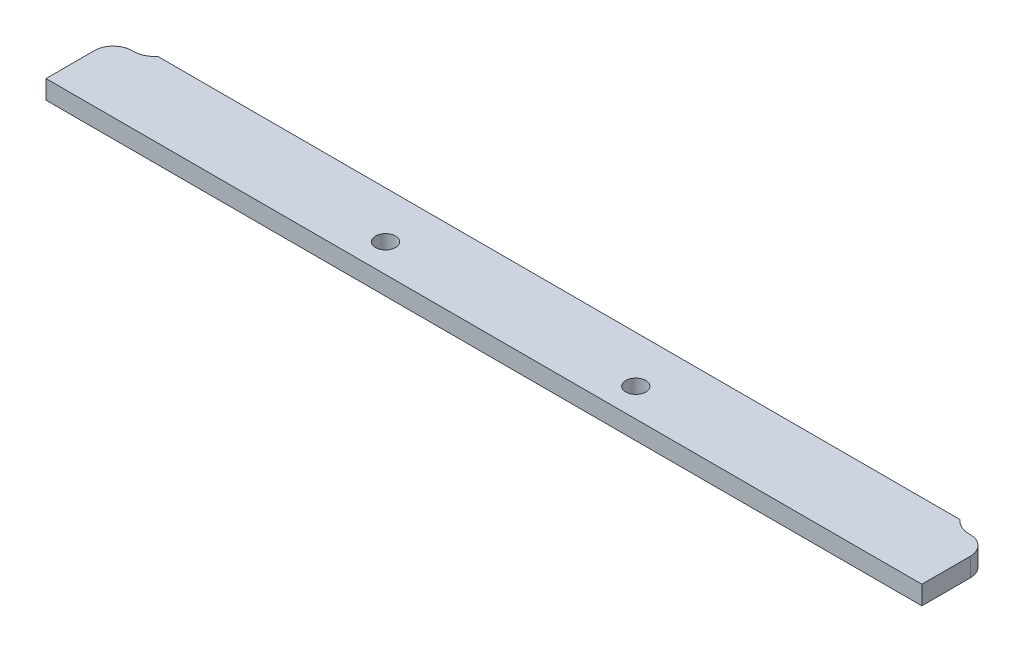
SolidWorks part; units mm, degrees
ref_plane "Front Plane" through (0, 0, 0) normal (0, 0, 1) x (1, 0, 0)
ref_plane "Top Plane" through (0, 0, 0) normal (0, 1, 0) x (1, 0, 0)
ref_plane "Right Plane" through (0, 0, 0) normal (1, 0, 0) x (0, 0, -1)
sketch "Sketch1" plane through (0, 0, 0) normal (0, 1, 0) x (1, 0, 0)
  line L0 (-5.431, 25.0999) -> (-5.6253, 25.0999) construction
  line L1 (128.3747, 25.0999) -> (128.1804, 25.0999) construction
  line L2 (131.3747, 22.0999) -> (131.3747, -33.8347) construction
  line L3 (131.3747, 14.3589) -> (-8.6253, 14.3589) construction
  line L4 (-8.6253, -33.8347) -> (-8.6253, 22.0999) construction
  line L5 (-2.7409, 26.3608) -> (125.4903, 26.3608) construction
  line L6 (-5.431, 25.0999) -> (-5.6253, 25.0999)
  line L7 (128.3747, 25.0999) -> (128.1804, 25.0999)
  line L8 (131.3747, 22.0999) -> (131.3747, 14.3589)
  line L9 (131.3747, 14.3589) -> (-8.6253, 14.3589)
  line L10 (-8.6253, 14.3589) -> (-8.6253, 22.0999)
  line L11 (-2.7409, 26.3608) -> (125.4903, 26.3608)
  arc A0 (-5.431, 25.0999) -> (-5.431, 32.0999) centre (-5.431, 28.5999) ccw construction
  arc A1 (128.1804, 32.0999) -> (128.1804, 25.0999) centre (128.1804, 28.5999) ccw construction
  arc A2 (131.3747, 22.0999) -> (128.3747, 25.0999) centre (128.3747, 22.0999) ccw construction
  arc A3 (-5.6253, 25.0999) -> (-8.6253, 22.0999) centre (-5.6253, 22.0999) ccw construction
  arc A4 (-5.431, 25.0999) -> (-2.7409, 26.3608) centre (-5.431, 28.5999) ccw
  arc A5 (125.4903, 26.3608) -> (128.1804, 25.0999) centre (128.1804, 28.5999) ccw
  arc A6 (131.3747, 22.0999) -> (128.3747, 25.0999) centre (128.3747, 22.0999) ccw
  arc A7 (-5.6253, 25.0999) -> (-8.6253, 22.0999) centre (-5.6253, 22.0999) ccw
extrude "Boss-Extrude1" add sketch "Sketch1" along normal blind 3
sketch "Sketch2" plane through (0, 0, 0) normal (0, -1, 0) x (1, 0, 0)
  text T0 "1"
extrude "Cut-Extrude1" cut sketch "Sketch2" against normal blind 1
sketch "Sketch3" plane through (0, 3, 0) normal (0, 1, 0) x (1, 0, 0)
  arc A2 (41.1098, 17.3031) -> (41.1098, 20.5031) centre (41.1098, 18.9031) ccw
  arc A3 (41.1098, 20.5031) -> (41.1098, 17.3031) centre (41.1098, 18.9031) ccw
  arc A4 (41.1098, 17.3031) -> (41.1098, 20.5031) centre (41.1098, 18.9031) ccw
  arc A5 (41.1098, 20.5031) -> (41.1098, 17.3031) centre (41.1098, 18.9031) ccw
  arc A6 (81.1098, 17.3031) -> (81.1098, 20.5031) centre (81.1098, 18.9031) ccw
  arc A7 (81.1098, 20.5031) -> (81.1098, 17.3031) centre (81.1098, 18.9031) ccw
  arc A8 (81.1098, 17.3031) -> (81.1098, 20.5031) centre (81.1098, 18.9031) ccw
  arc A9 (81.1098, 20.5031) -> (81.1098, 17.3031) centre (81.1098, 18.9031) ccw
  dimension "D1" = 0
  dimension "D2" = 0
extrude "Cut-Extrude2" cut sketch "Sketch3" against normal up to next
